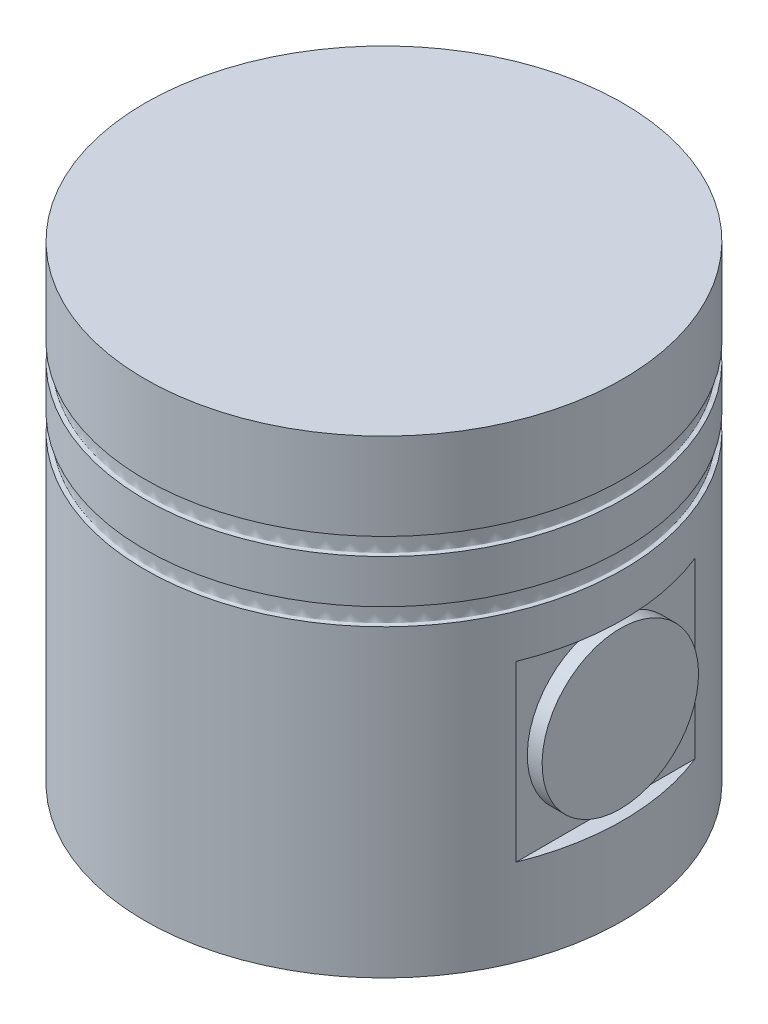
SolidWorks part; units mm, degrees
ref_plane "Front Plane" through (0, 0, 0) normal (0, 0, 1) x (1, 0, 0)
ref_plane "Top Plane" through (0, 0, 0) normal (0, 1, 0) x (1, 0, 0)
ref_plane "Right Plane" through (0, 0, 0) normal (1, 0, 0) x (0, 0, -1)
sketch "Sketch2" plane through (0, 0, 0) normal (0, 0, 1) x (1, 0, 0)
  line L1 (27.5, 42) -> (27, 42) construction
  line L2 (27, 42) -> (27, 44) construction
  line L3 (27, 44) -> (27.5, 44) construction
  line L5 (27.5, 35) -> (27, 35) construction
  line L6 (27, 35) -> (27, 37) construction
  line L7 (27, 37) -> (27.5, 37) construction
  line L9 (27.5, 54) -> (0, 54)
  line L10 (0, 54) -> (0, 51.5)
  line L11 (0, 51.5) -> (25, 51.5)
  line L12 (25, 51.5) -> (25, 0)
  line L13 (25, 0) -> (27.5, 0)
  line L14 (27.5, 54) -> (27.5, 44)
  line L15 (27.5, 42) -> (27.5, 37)
  line L16 (27.5, 35) -> (27.5, 0)
  spline S0 degree 3 poles (27.5, 44) (27.3415, 44) (27.1792, 44) (27.013, 44) (27, 43.987) (27, 43.329) (27, 42.671) (27, 42.013) (27.013, 42) (27.1792, 42) (27.3415, 42) (27.5, 42) knots 0 0 0 0 0.16003 0.163917 0.167805 0.171693 0.828307 0.832195 0.836083 0.83997 1 1 1 1
  spline S1 degree 3 poles (27.5, 37) (27.3415, 37) (27.1792, 37) (27.013, 37) (27, 36.987) (27, 36.329) (27, 35.671) (27, 35.013) (27.013, 35) (27.1792, 35) (27.3415, 35) (27.5, 35) knots 0 0 0 0 0.16003 0.163917 0.167805 0.171693 0.828307 0.832195 0.836083 0.83997 1 1 1 1
  dimension "D1" = 2.5
  dimension "D2" = 5
  dimension "D3" = 2
  dimension "D4" = 2.5
  dimension "D5" = 10
  dimension "D6" = 35
  dimension "D7" = 25
  dimension "D8" = 27.5
  dimension "D9" = 0.5
  dimension "D10" = 2
revolve "Revolve1" add sketch "Sketch2" angle 360 about L10
sketch "Sketch4" plane through (0, 0, 0) normal (0, 0, 1) x (1, 0, 0)
  line L0 (-27.5, 30) -> (-25.5, 30)
  line L1 (-25.5, 30) -> (-25.5, 10)
  line L2 (-25.5, 10) -> (-27.5, 10)
  line L3 (-27.5, 35) -> (-27.5, 0) construction
  line L4 (-27.5, 30) -> (-27.5, 10)
  line L5 (-27.5, 0) -> (27.5, 0) construction
  point P4 (-26.5, 30)
  dimension "D1" = 2
  dimension "D2" = 20
  dimension "D3" = 10
extrude "Cut-Extrude1" cut sketch "Sketch4" against normal through all both and the other way through all contours L1 L2 L4 L0
mirror "Mirror1" about plane through (0, 0, 0) normal (1, 0, 0) of "Cut-Extrude1"
sketch "Sketch5" plane through (-25.5, 0, 0) normal (-1, 0, 0) x (0, 0, 1)
  line L0 (-27.5, 0) -> (27.5, 0) construction
  circle A0 centre (0, 20) radius 9
  dimension "D1" = 18
  dimension "D2" = 20
extrude "Cut-Extrude2" cut sketch "Sketch5" against normal up to surface (51 mm away) contours A0 up to face at (25.5, 20, 0)
sketch "Sketch6" plane through (-25.5, 0, 0) normal (-1, 0, 0) x (0, 0, 1)
  circle A0 centre (0, 20) radius 9 construction
  circle A1 centre (0, 20) radius 9
extrude "Boss-Extrude1" add sketch "Sketch6" along normal blind 1.7 and the other way blind 52.7 separate body contours A1
